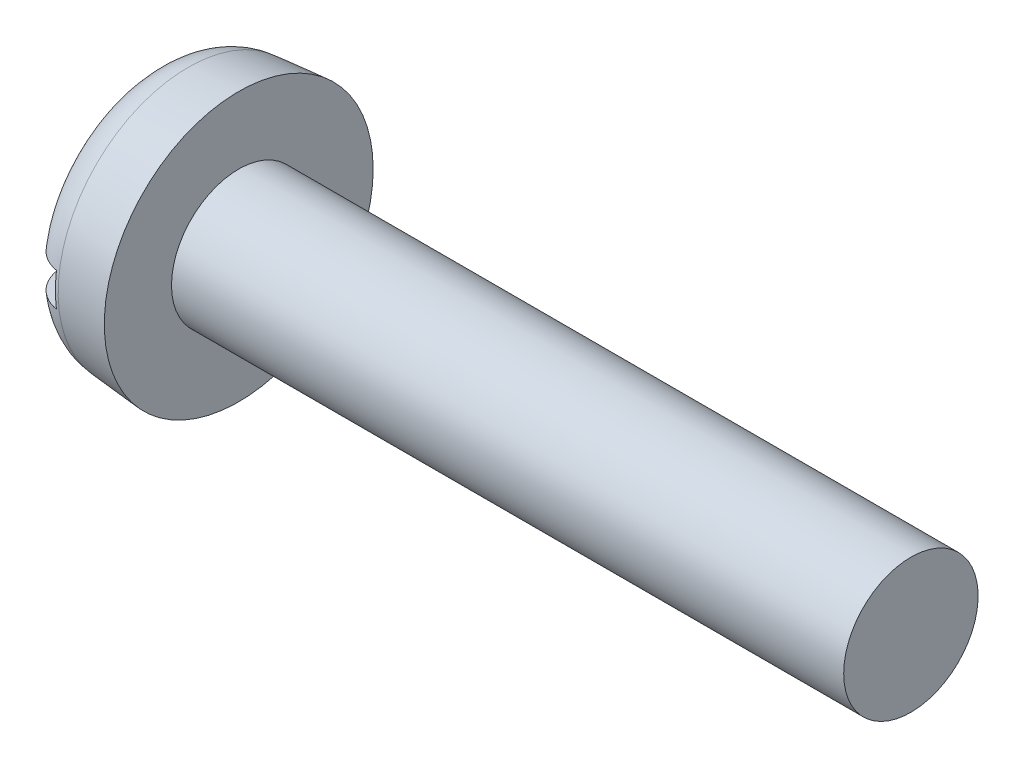
SolidWorks part; units mm, degrees
ref_plane "Plane1" through (0, 0, 0) normal (0, 0, 1) x (1, 0, 0)
ref_plane "Plane2" through (0, 0, 0) normal (0, 1, 0) x (1, 0, 0)
ref_plane "Plane3" through (0, 0, 0) normal (1, 0, 0) x (0, 0, -1)
sketch "BodySke" plane through (0, 0, 0) normal (0, 0, 1) x (1, 0, 0)
  line L0 (1.3, 1) -> (1.3, 2)
  line L1 (0, 0) -> (0, 1.8863)
  line L2 (-25.4, 0) -> (127, 0) construction
  line L3 (11.3, 0) -> (0, 0)
  line L4 (1.3, 1) -> (11.3, 1)
  line L5 (11.3, 1) -> (11.3, 0)
  line L6 (0, 1.8863) -> (1.3, 2)
  line L9 (1.7, 2.5875) -> (1.7, -6.9375) construction
  line L10 (1.3, 6.35) -> (1.3, -3.175) construction
  dimension "Length" = 10
  dimension "Head_ht" = 1.3
  dimension "Advance" = 0.4
  dimension "Thread_nom" = 10
  dimension "Head_dia" = 4
  dimension "Head_side_angle" = 5
  dimension "Diameter" = 2
revolve "Base-Revolve" add sketch "BodySke"
cosmetic thread "ThreadCosmetic" [suppressed]
fillet "Fillet1" [suppressed] radius 0.1
fillet "Fillet2" radius 0.6 1 edges at (0, 0, 1.8863)
sketch "Sketch2" plane through (0, 0, 0) normal (1, 0, 0) x (0, 0, -1)
  line L0 (2, -0.25) -> (-2, -0.25)
  line L1 (2, -0.25) -> (2, 0.25)
  line L2 (-2, 0.25) -> (2, 0.25)
  line L3 (-2, 0.25) -> (-2, -0.25)
  dimension "D1" = 4
  dimension "Slot_width" = 0.5
  dimension "D2" = 2
  dimension "D3" = 0.25
extrude "Slot" cut sketch "Sketch2" along normal blind 0.5
sketch "ThdSchSke" plane through (0, 0, 0) normal (0, 0, 1) x (1, 0, 0)
  line L0 (2.1, -0.774) -> (1.9418, -1)
  line L1 (2.1, -0.774) -> (2.2582, -1)
  line L2 (2.2582, -1) -> (2.2582, -1.25)
  line L3 (-3.175, 0) -> (5.1513, 0) construction
  line L5 (2.2582, -1.25) -> (1.9418, -1.25)
  line L6 (1.9418, -1.25) -> (1.9418, -1)
  dimension "Diameter" = 2
  dimension "SideAngle" = 55
  dimension "VeeAngle" = 70
  dimension "Thread_minor" = 1.548
  dimension "Overcut" = 2.5
  dimension "Start" = 2.1
revolve "ThreadSchematic" [suppressed] cut sketch "ThdSchSke" angle 360 about L3
pattern_linear "ThdSchPat" [suppressed]
equation "\"D1@Sketch2\" = \"Head_dia@BodySke\""
equation "\"D2@Sketch2\" = \"D1@Sketch2\" / 2"
equation "\"D3@Sketch2\" = \"Slot_width@Sketch2\" / 2"
equation "\"Thread_length@ThreadCosmetic\" = ((sgn( (\"Length@BodySke\" - \"Advance@BodySke\" * 2.0 ) - \"Thread_nom@BodySke\" )-1)*( (\"Length@BodySke\" - \"Advance@BodySke\"  * 2.0) - \"Thread_nom@BodySke\" ))/-2+ \"Thread_nom@BodySke\""
equation "\"Thread_minor@ThdSchSke\" = \"Thread_minor@ThreadCosmetic\""
equation "\"Diameter@ThdSchSke\" = \"Diameter@BodySke\""
equation "\"Overcut@ThdSchSke\" = \"Diameter@BodySke\" * 1.25"
equation "\"Start@ThdSchSke\" = \"Head_ht@BodySke\" + \"Length@BodySke\" - \"Thread_length@ThreadCosmetic\"  '---Non-countersunk---"
equation "\"Num_threads@ThdSchPat\" = int( \"Thread_length@ThreadCosmetic\" / \"Advance@BodySke\" + 0.999 )  + 1"
equation "\"Advance@ThdSchPat\" = \"Thread_length@ThreadCosmetic\" /  (\"Num_threads@ThdSchPat\" - 1) 'relax it"
